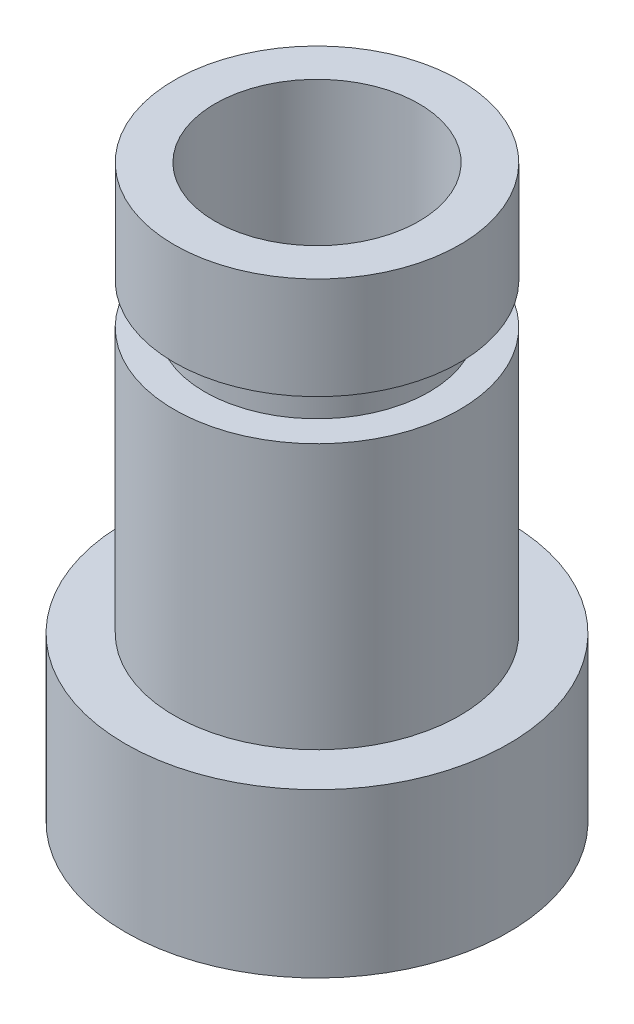
SolidWorks part; units mm, degrees
material "Plain Carbon Steel"
ref_plane "Front Plane" through (0, 0, 0) normal (0, 0, 1) x (1, 0, 0)
ref_plane "Top Plane" through (0, 0, 0) normal (0, 1, 0) x (1, 0, 0)
ref_plane "Right Plane" through (0, 0, 0) normal (1, 0, 0) x (0, 0, -1)
sketch "Sketch1" plane through (0, 0, 0) normal (0, 1, 0) x (1, 0, 0)
  circle A0 centre (0, 0) radius 4.7
  dimension "D1" = 9.4
extrude "Boss-Extrude1" add sketch "Sketch1" along normal blind 4
sketch "Sketch2" plane through (0, 4, 0) normal (0, 1, 0) x (1, 0, 0)
  circle A0 centre (0, 0) radius 3.5
  dimension "D1" = 7
extrude "Boss-Extrude2" add sketch "Sketch2" along normal blind 6.5
sketch "Sketch3" plane through (0, 10.5, 0) normal (0, 1, 0) x (1, 0, 0)
  circle A0 centre (0, 0) radius 2.75
  dimension "D1" = 5.5
extrude "Boss-Extrude3" add sketch "Sketch3" along normal blind 1
sketch "Sketch4" plane through (0, 11.5, 0) normal (0, 1, 0) x (1, 0, 0)
  circle A0 centre (0, 0) radius 3.5
  dimension "D1" = 7
extrude "Boss-Extrude4" add sketch "Sketch4" along normal blind 2.5
sketch "Sketch5" plane through (0, 14, 0) normal (0, 1, 0) x (1, 0, 0)
  circle A0 centre (0, 0) radius 2.5
  dimension "D1" = 5
extrude "Cut-Extrude1" cut sketch "Sketch5" against normal through all
